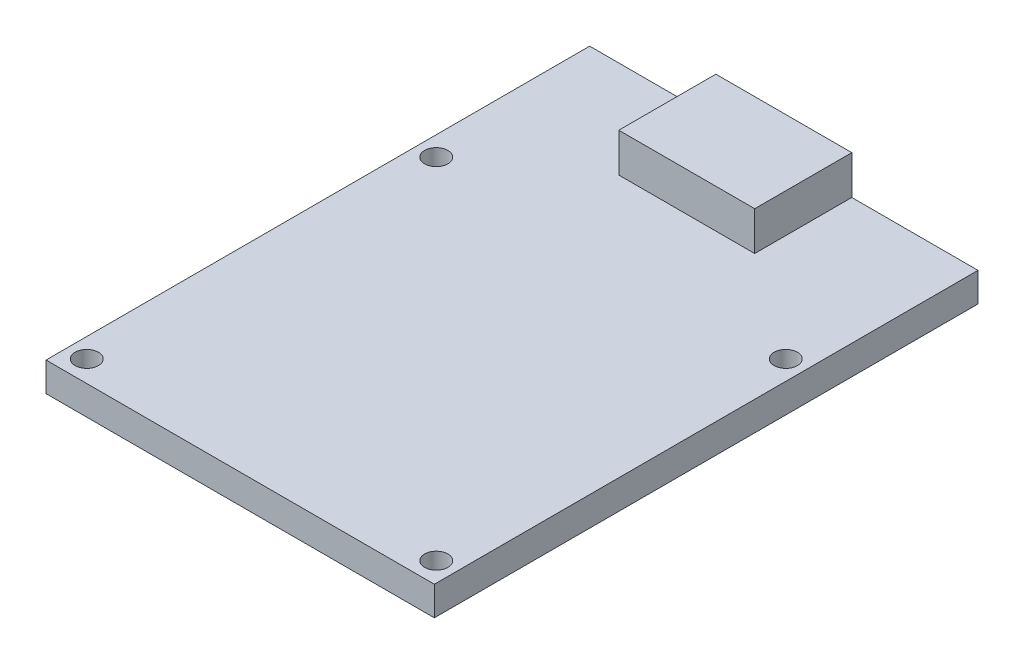
SolidWorks part; units mm, degrees
material "PBT 一般用途"
ref_plane "前视基准面" through (0, 0, 0) normal (0, 0, 1) x (1, 0, 0)
ref_plane "上视基准面" through (0, 0, 0) normal (0, 1, 0) x (1, 0, 0)
ref_plane "右视基准面" through (0, 0, 0) normal (1, 0, 0) x (0, 0, -1)
sketch "草图1" plane through (0, 0, 0) normal (0, 1, 0) x (1, 0, 0)
  line L1 (-20, 28) -> (20, 28)
  line L2 (-20, 28) -> (-20, -28)
  line L3 (-20, -28) -> (20, -28)
  line L4 (20, 28) -> (20, -28)
  line L5 (-20, 28) -> (20, -28) construction
  line L6 (-20, -28) -> (20, 28) construction
  point P0 (0, 0)
  dimension "D1" = 40
  dimension "D2" = 56
extrude "凸台-拉伸1" add sketch "草图1" along normal blind 3
sketch "草图2" plane through (0, 3, 0) normal (0, 1, 0) x (1, 0, 0)
  line L0 (-20, 28) -> (-20, -28) construction
  line L1 (-20, -28) -> (20, -28) construction
  line L2 (20, -28) -> (20, 28) construction
  line L3 (-18, -25.8) -> (-18, 10.2)
  line L4 (18, -25.8) -> (18, 10.2)
  point P0 (-18, -25.8)
  point P1 (18, -25.8)
  dimension "D1" = 2
  dimension "D2" = 2.2
  dimension "D3" = 2.2
  dimension "D4" = 2
  dimension "D5" = 36
  dimension "D6" = 36
sketch "草图3" plane through (0, 3, 0) normal (0, 1, 0) x (1, 0, 0)
  point P0 (-18, 10.2)
  point P3 (18, 10.2)
  point P6 (18, -25.8)
  point P9 (-18, -25.8)
hole_wizard "孔1" positions "草图3" profile "草图4" legacy end condition up to next
sketch "草图4" plane through (-18, 3, -10.2) normal (1, 0, 0) x (0, 0, 1)
  line L0 (0, 0) -> (0, 3)
  line L1 (0, 3) -> (1.2, 3)
  line L2 (1.2, 3) -> (1.2, 0)
  line L3 (1.2, 0) -> (0, 0)
  line L4 (0, 110) -> (0, -10) construction
  dimension "直径" = 2.4
  dimension "深度" = 3
sketch "草图5" plane through (0, 3, 0) normal (0, 1, 0) x (1, 0, 0)
  line L0 (20, 28) -> (-20, 28) construction
  line L1 (0, 28) -> (0, 23)
  line L3 (-7, 18) -> (7, 18)
  line L4 (-7, 18) -> (-7, 28)
  line L5 (-7, 28) -> (7, 28)
  line L6 (7, 18) -> (7, 28)
  line L7 (-7, 18) -> (7, 28) construction
  line L8 (-7, 28) -> (7, 18) construction
  point P0 (0, 28)
  dimension "D1" = 5
  dimension "D2" = 14
extrude "凸台-拉伸2" add sketch "草图5" along normal blind 4
